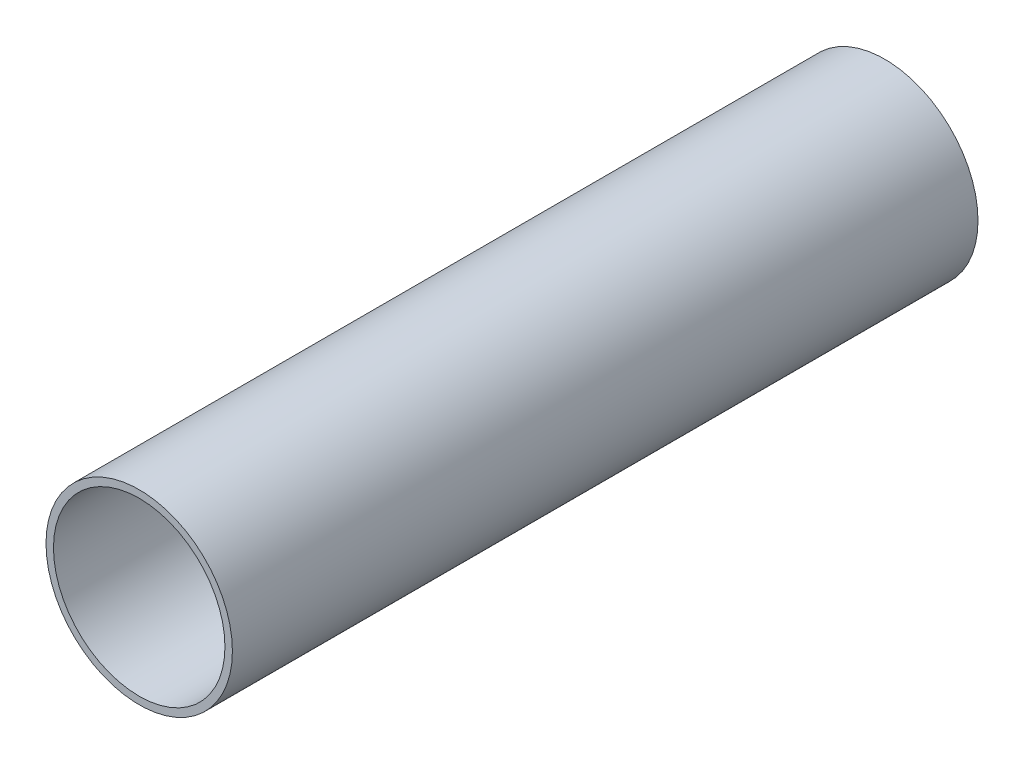
SolidWorks part; units mm, degrees
ref_plane "前视基准面" through (0, 0, 0) normal (0, 0, 1) x (1, 0, 0)
ref_plane "上视基准面" through (0, 0, 0) normal (0, 1, 0) x (1, 0, 0)
ref_plane "右视基准面" through (0, 0, 0) normal (1, 0, 0) x (0, 0, -1)
sketch "草图2" plane through (0, 0, 0) normal (0, 0, 1) x (1, 0, 0)
  circle A0 centre (0, 0) radius 25
  circle A1 centre (0, 0) radius 23
  dimension "D1" = 50
  dimension "D2" = 2
extrude "凸台-拉伸1" add sketch "草图2" along normal blind 200
